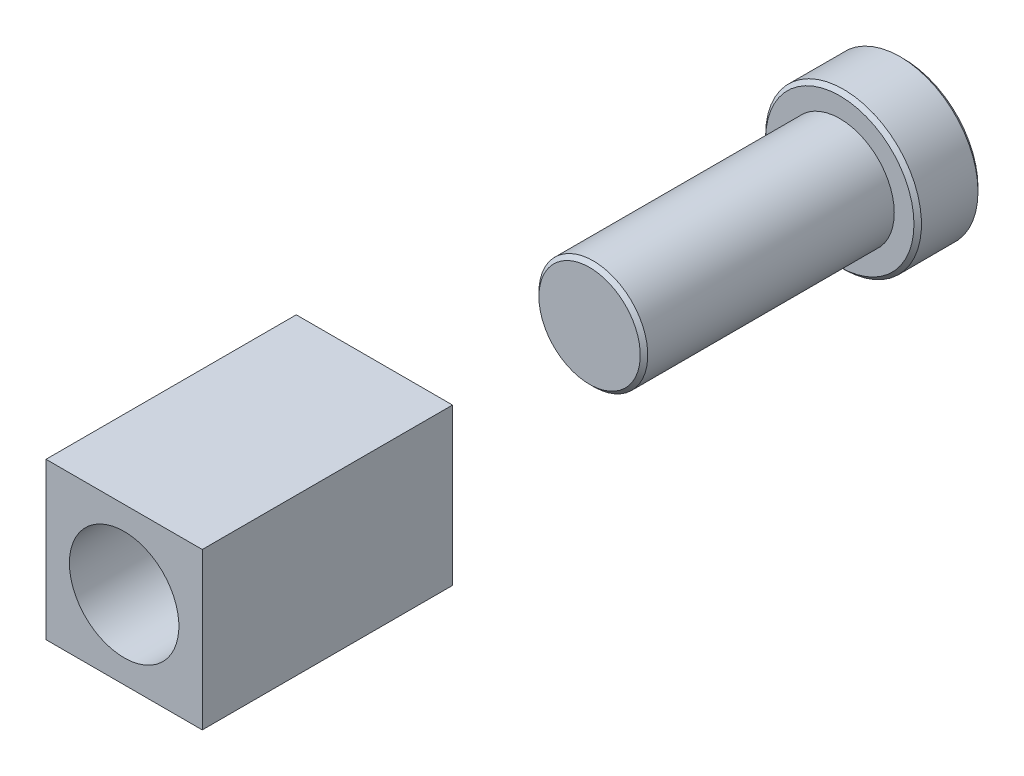
SolidWorks part; units mm, degrees
ref_plane "Front Plane" through (0, 0, 0) normal (0, 0, 1) x (1, 0, 0)
ref_plane "Top Plane" through (0, 0, 0) normal (0, 1, 0) x (1, 0, 0)
ref_plane "Right Plane" through (0, 0, 0) normal (1, 0, 0) x (0, 0, -1)
sketch "Sketch1" plane through (0, 0, 0) normal (0, 0, 1) x (1, 0, 0)
  circle A0 centre (0, 0) radius 15.8115
  dimension "D1" = 31.623
extrude "Boss-Extrude1" add sketch "Sketch1" along normal blind 12.9988
sketch "Sketch2" plane through (0, 0, 12.9988) normal (0, 0, 1) x (1, 0, 0)
  circle A0 centre (0, 0) radius 11.049
  dimension "D1" = 22.098
extrude "Boss-Extrude2" add sketch "Sketch2" along normal blind 50.8
ref_plane "Plane1" through (0, 0, 107.4833) normal (0, 0, 1) x (1, 0, 0)
sketch "Sketch3" plane through (0, 0, 107.4833) normal (0, 0, 1) x (1, 0, 0)
  line L0 (15.8613, -15.8613) -> (-15.8613, 15.8613) construction
  line L1 (-15.8613, 15.8613) -> (15.8613, 15.8613)
  line L2 (-15.8613, 15.8613) -> (-15.8613, -15.8613)
  line L3 (-15.8613, -15.8613) -> (15.8613, -15.8613)
  line L4 (15.8613, 15.8613) -> (15.8613, -15.8613)
extrude "Boss-Extrude3" add sketch "Sketch3" along normal blind 50.8 separate body
sketch "Sketch4" plane through (0, 0, 107.4833) normal (0, 0, -1) x (-1, 0, 0)
  circle A0 centre (0, 0) radius 11.1125
  dimension "D1" = 22.225
extrude "Cut-Extrude1" cut sketch "Sketch4" against normal through all
chamfer "Chamfer1" distance 0.762 angle 45 3 edges at (15.8115, 0, 0) (15.8115, 0, 12.9988) (11.049, 0, 63.7988)
equation "\"销轴直径\" = 0.87in"
equation "\"基体长度\"= \"D1@Boss-Extrude3\""
equation "\"D1@Sketch1\"= \"销轴直径\" + .375'销钉直径比销轴直径大0.375英寸"
equation "\"D1@Boss-Extrude1\"=\"销轴直径\" / 1.7in"
equation "\"D1@Boss-Extrude2\"= \"基体长度\""
equation "\"D1@Sketch4\"= \"销轴直径\" + 0.005"
equation "\"D1@Sketch2\"= \"销轴直径\""
equation "\"Chamfer1\" = IIF ( \"销轴直径\" < 1mm , \"suppressed\" , \"unsuppressed\" )"
